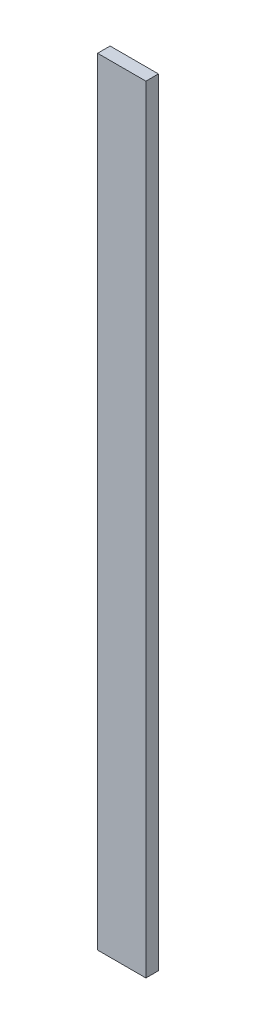
SolidWorks part; units mm, degrees
ref_plane "Front Plane" through (0, 0, 0) normal (0, 0, 1) x (1, 0, 0)
ref_plane "Top Plane" through (0, 0, 0) normal (0, 1, 0) x (1, 0, 0)
ref_plane "Right Plane" through (0, 0, 0) normal (1, 0, 0) x (0, 0, -1)
sketch "Sketch1" plane through (0, 0, 0) normal (0, 1, 0) x (1, 0, 0)
  line L1 (24.5, 6.35) -> (-24.5, 6.35)
  line L2 (24.5, 6.35) -> (24.5, -6.35)
  line L3 (24.5, -6.35) -> (-24.5, -6.35)
  line L4 (-24.5, 6.35) -> (-24.5, -6.35)
  line L5 (24.5, 6.35) -> (-24.5, -6.35) construction
  line L6 (24.5, -6.35) -> (-24.5, 6.35) construction
  point P0 (0, 0)
  dimension "D1" = 12.7
  dimension "D2" = 49
extrude "Boss-Extrude1" add sketch "Sketch1" along normal blind 787.4
